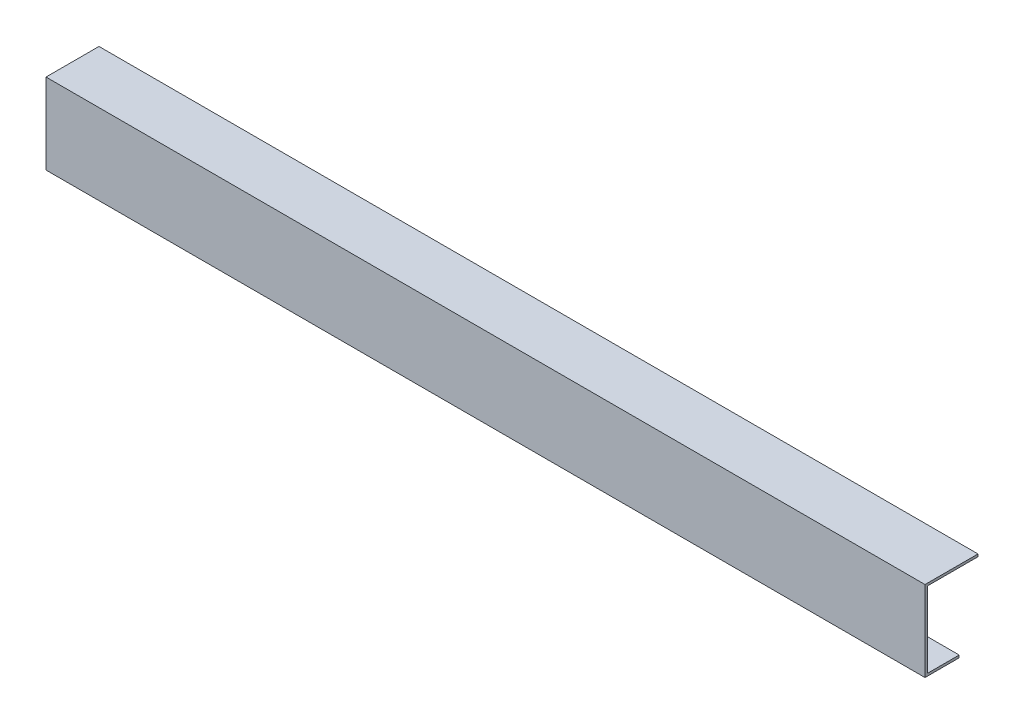
SolidWorks part; units mm, degrees
ref_plane "Front Plane" through (0, 0, 0) normal (0, 0, 1) x (1, 0, 0)
ref_plane "Top Plane" through (0, 0, 0) normal (0, 1, 0) x (1, 0, 0)
ref_plane "Right Plane" through (0, 0, 0) normal (1, 0, 0) x (0, 0, -1)
sketch "Sketch1" plane through (0, 0, 0) normal (0, 0, 1) x (1, 0, 0)
  line L1 (0, 0) -> (914.4, 0)
  line L2 (0, 0) -> (0, -83.82)
  line L3 (0, -83.82) -> (914.4, -83.82)
  line L4 (914.4, 0) -> (914.4, -83.82)
  dimension "D1" = 83.82
  dimension "D2" = 914.4
extrude "Boss-Extrude1" add sketch "Sketch1" along normal blind 55.118
sketch "Sketch2" plane through (914.4, 0, 0) normal (1, 0, 0) x (0, 0, -1)
  line L0 (-19.558, -83.82) -> (-19.558, -81.28)
  line L1 (-55.118, -83.82) -> (0, -83.82) construction
  line L2 (-19.558, -81.28) -> (-52.578, -81.28)
  line L3 (-52.578, -81.28) -> (-52.578, -2.54)
  line L4 (-52.578, -2.54) -> (0, -2.54)
  line L5 (0, -83.82) -> (0, 0) construction
  line L6 (0, -2.54) -> (0, -83.82)
  line L7 (0, -83.82) -> (-19.558, -83.82)
  line L8 (-55.118, -83.82) -> (-55.118, 0) construction
  line L9 (-55.118, 0) -> (0, 0) construction
  dimension "D1" = 35.56
  dimension "D2" = 2.54
  dimension "D3" = 2.54
  dimension "D4" = 2.54
extrude "Cut-Extrude1" cut sketch "Sketch2" against normal through all
